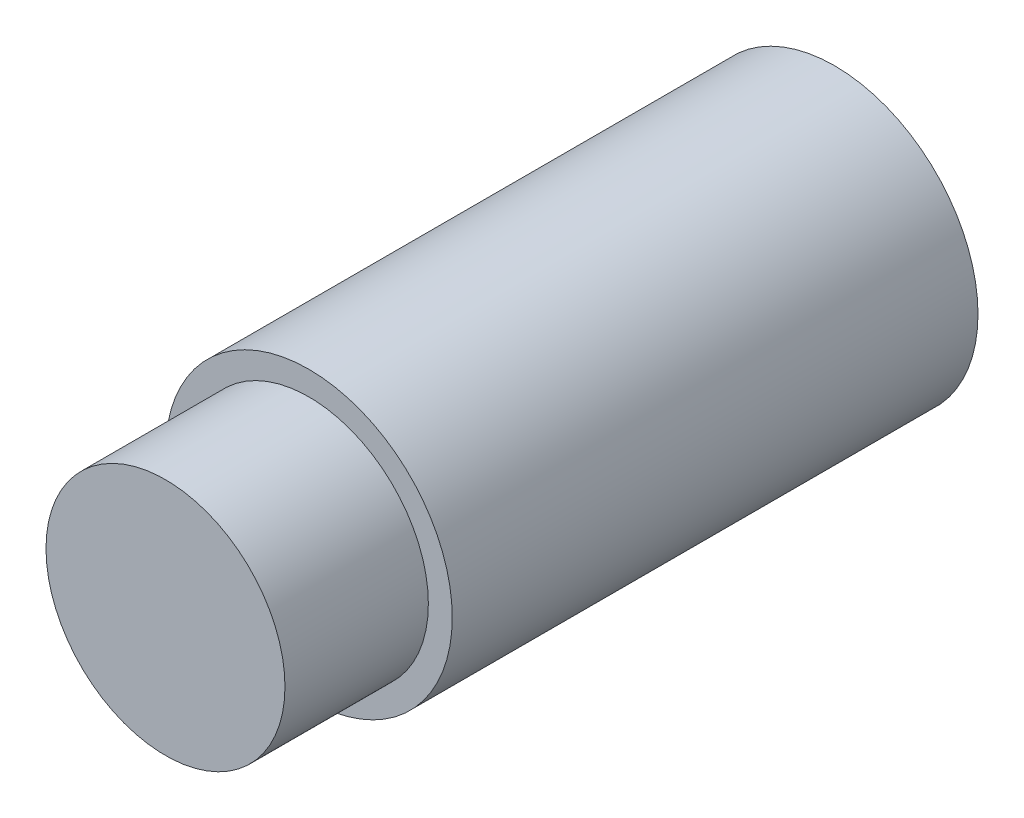
SolidWorks part; units mm, degrees
ref_plane "Piano frontale" through (0, 0, 0) normal (0, 0, 1) x (1, 0, 0)
ref_plane "Piano superiore" through (0, 0, 0) normal (0, 1, 0) x (1, 0, 0)
ref_plane "Piano destro" through (0, 0, 0) normal (1, 0, 0) x (0, 0, -1)
sketch "Schizzo1" plane through (0, 0, 0) normal (0, 0, 1) x (1, 0, 0)
  circle A0 centre (0, 0) radius 3
  dimension "D1" = 6
extrude "Estrusione-Estrusione1" add sketch "Schizzo1" along normal blind 11
sketch "Schizzo2" plane through (0, 0, 11) normal (0, 0, 1) x (1, 0, 0)
  circle A0 centre (0, 0) radius 2.5
  dimension "D1" = 5
extrude "Estrusione-Estrusione2" add sketch "Schizzo2" along normal blind 3
